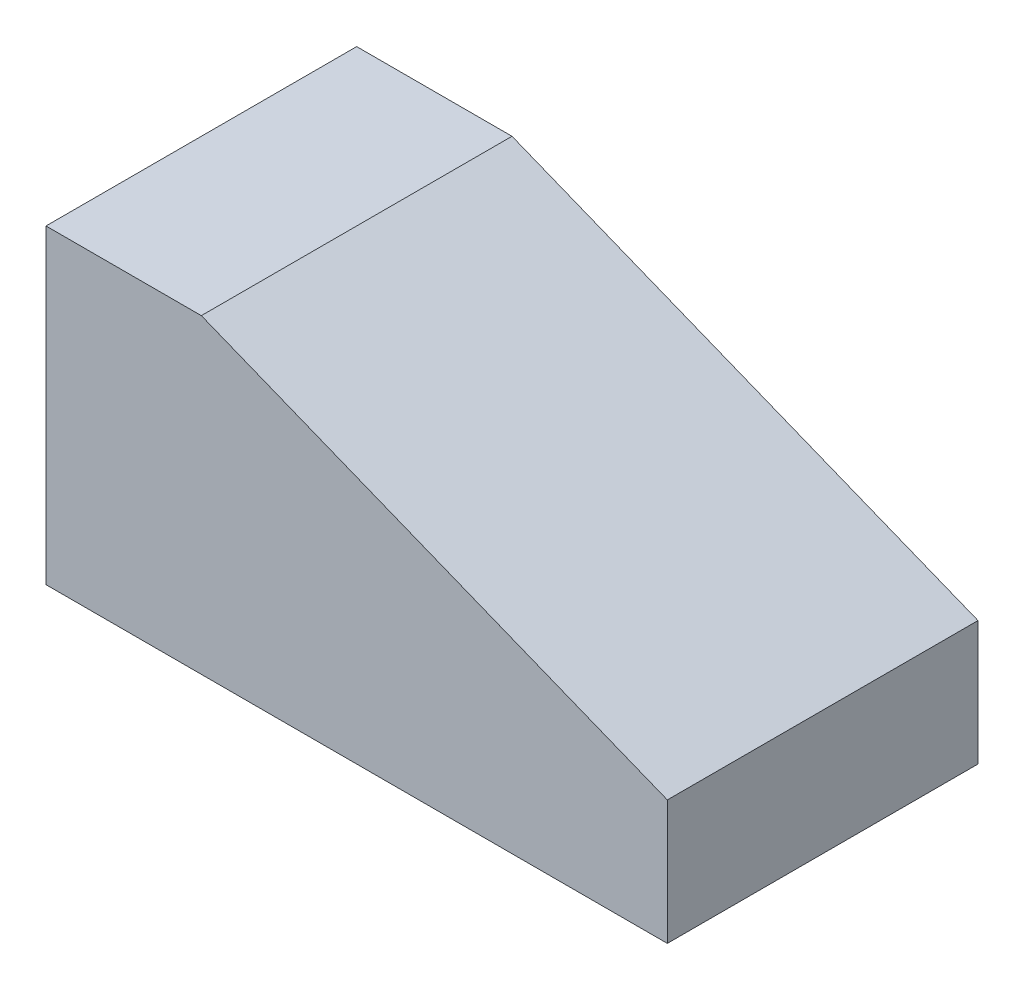
SolidWorks part; units mm, degrees
ref_plane "Front Plane" through (0, 0, 0) normal (0, 0, 1) x (1, 0, 0)
ref_plane "Top Plane" through (0, 0, 0) normal (0, 1, 0) x (1, 0, 0)
ref_plane "Right Plane" through (0, 0, 0) normal (1, 0, 0) x (0, 0, -1)
sketch "Sketch2" plane through (0, 0, 0) normal (0, 0, 1) x (1, 0, 0)
  line L0 (0, 0) -> (100, 0)
  line L1 (100, 0) -> (100, 20)
  line L2 (100, 20) -> (25, 50)
  line L3 (25, 50) -> (0, 50)
  line L4 (0, 50) -> (0, 0)
  dimension "D1" = 25
  dimension "D2" = 50
  dimension "D3" = 100
  dimension "D4" = 20
extrude "Boss-Extrude1" add sketch "Sketch2" along normal blind 50
